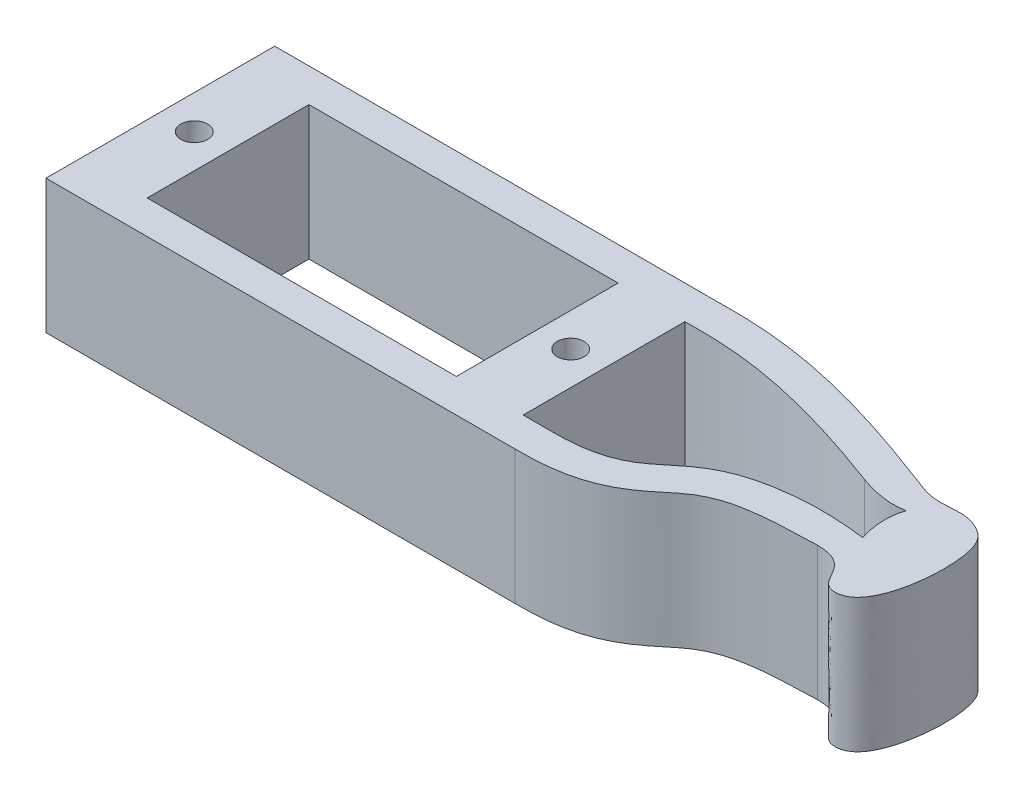
SolidWorks part; units mm, degrees
ref_plane "Front" through (0, 0, 0) normal (0, 0, 1) x (1, 0, 0)
ref_plane "Bottom" through (0, 0, 0) normal (0, 1, 0) x (1, 0, 0)
ref_plane "Right" through (0, 0, 0) normal (1, 0, 0) x (0, 0, -1)
other "Configuration Table"
sketch "Sketch 1" plane through (0, 0, 0) normal (0, 1, 0) x (1, 0, 0)
  line L0 (0, 0) -> (0, -12.0852)
  line L1 (0, -12.0852) -> (23.1, -12.0852)
  line L2 (0, -12.0852) -> (28.092, -12.0852) construction
  line L3 (28.092, -12.0852) -> (28.092, 0) construction
  line L4 (0, 0) -> (23.1, 0)
  line L5 (23.1, -6.0426) -> (28.1, -6.0425) construction
  line L7 (-2.5, 2.5) -> (28.0711, 2.5)
  line L9 (-2.5, -14.5852) -> (29.9653, -14.5852)
  line L11 (47.4956, -1.7574) -> (47.4956, -9.5141) construction
  line L13 (28.092, -12.0852) -> (29.9852, -12.0852)
  line L14 (0, -6.0426) -> (-5.0616, -6.0426) construction
  line L15 (23.1, -12.0852) -> (23.1, 0)
  line L16 (0, -12.0852) -> (29.9852, -12.0852) construction
  line L17 (0, 0) -> (28.092, 0) construction
  line L18 (44.9956, -3.4912) -> (44.9956, -7.1076) construction
  line L19 (-2.5, 2.5) -> (-5.0616, 2.5)
  line L20 (-5.0616, 2.5) -> (-5.0616, -14.5852)
  line L21 (-5.0616, -14.5852) -> (-2.5, -14.5852)
  line L22 (28.092, 0) -> (28.092, -12.0852)
  line L23 (-2.5, 2.5) -> (-2.5, -14.5852) construction
  circle A0 centre (-2.5308, -6.0426) radius 1
  circle A1 centre (25.6, -6.0425) radius 1
  spline S0 degree 3 poles (29.9852, -12.0852) (38.2811, -12.2209) (35.1108, -7.4841) (44.9956, -7.1076) knots 0 0 0 0 1 1 1 1
  spline S1 degree 3 poles (28.092, 0) (31.819, 0.063) (36.0838, -0.1566) (44.9956, -3.4912) knots 0.142072 0.142072 0.142072 0.142072 1 1 1 1
  spline S2 degree 1 poles (28.0711, 2.5) (47.4956, -1.7574) knots 0 0 1 1 construction
  spline S3 degree 1 poles (29.9653, -14.5852) (47.4956, -9.5141) knots 0 0 1 1 construction
  spline S4 degree 3 poles (28.0711, 2.5) (28.332, 2.5043) (28.8455, 2.5102) (29.9391, 2.5047) (31.9844, 2.4293) (34.7093, 2.1036) (37.9743, 1.3886) (40.7527, 0.6193) (43.895, -0.4047) (46.3257, -1.3196) (47.4956, -1.7574) knots 0.143652 0.143652 0.143652 0.143652 0.200431 0.257209 0.370766 0.597881 0.711438 0.824995 0.938552 1.052109 1.052109 1.052109 1.052109
  spline S5 degree 3 poles (47.4956, -9.5141) (46.8282, -9.5396) (45.998, -9.5722) (44.9894, -9.6088) (44.4121, -9.6373) (43.4555, -9.7113) (42.3284, -9.8699) (40.9309, -10.2053) (39.8239, -10.699) (38.8526, -11.3917) (37.6744, -12.4203) (36.1766, -13.4305) (34.6082, -14.0479) (33.267, -14.3781) (31.9957, -14.5341) (30.8821, -14.5875) (30.2659, -14.5898) (29.9653, -14.5852) knots 0.000759 0.000759 0.000759 0.000759 0.06828 0.08516 0.10204 0.135801 0.203322 0.270843 0.405885 0.540927 0.675969 0.811011 0.878532 0.946053 1.013574 1.047335 1.081095 1.081095 1.081095 1.081095
  spline S6 degree 3 poles (47.4956, -1.7574) (49.7784, -2.7017) (50.7289, -1.2991) (54.2886, -3.8385) (53.749, -11.6342) (49.5533, -12.1452) (50.183, -9.4805) (47.4956, -9.5141) knots 0 0 0 0 0.410599 0.487696 0.739498 0.793876 1 1 1 1
  spline S7 degree 2 poles (44.9956, -7.1076) (46.5345, -7.0839) (48.7103, -7.3258) knots 0 0 0 1 1 1
  spline S8 degree 2 poles (44.9956, -3.4912) (47.1194, -4.2651) (48.5973, -3.9631) knots 0 0 0 1 1 1
  spline S9 degree 3 poles (48.7103, -7.3258) (48.3453, -6.1976) (48.2431, -5.0095) (48.5973, -3.9631) knots 0 0 0 0 1 1 1 1
  dimension "D1" = 2.5
extrude "Extruded Base 1" add sketch "Sketch 1" along normal blind 10
